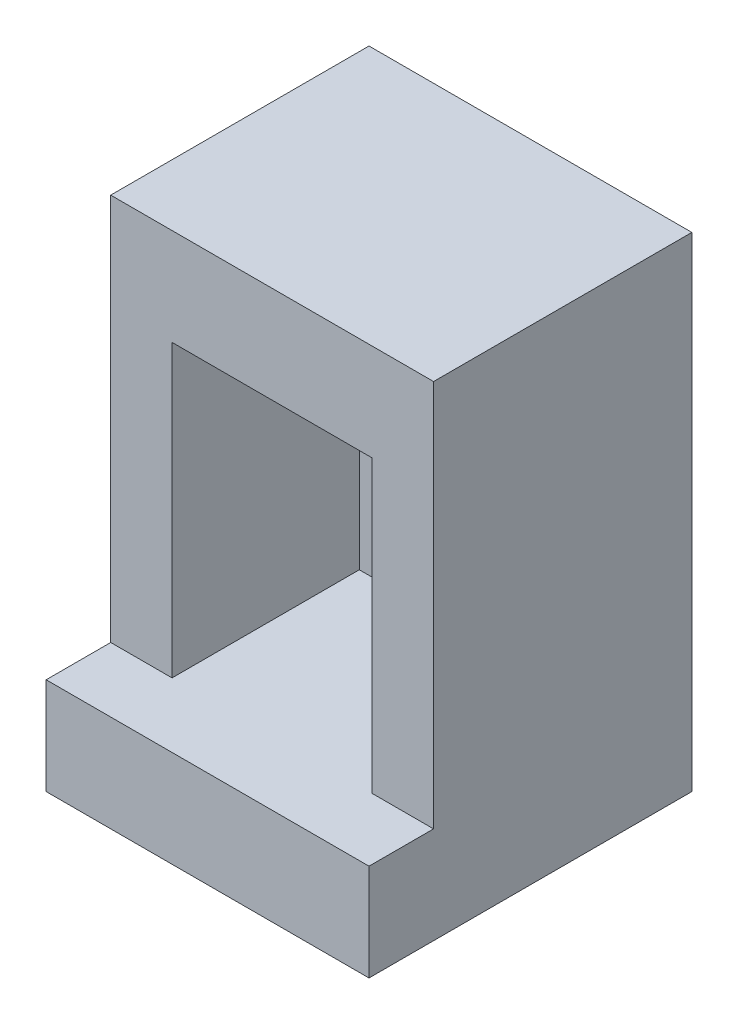
SolidWorks part; units mm, degrees
ref_plane "Front Plane" through (0, 0, 0) normal (0, 0, 1) x (1, 0, 0)
ref_plane "Top Plane" through (0, 0, 0) normal (0, 1, 0) x (1, 0, 0)
ref_plane "Right Plane" through (0, 0, 0) normal (1, 0, 0) x (0, 0, -1)
sketch "Sketch1" plane through (0, 0, 0) normal (0, 1, 0) x (1, 0, 0)
  line L1 (0, 0) -> (10, 0)
  line L2 (0, 0) -> (0, 10)
  line L3 (0, 10) -> (10, 10)
  line L4 (10, 0) -> (10, 10)
  dimension "D1" = 10
  dimension "D2" = 10
extrude "Boss-Extrude1" add sketch "Sketch1" along normal blind 3
sketch "Sketch2" plane through (0, 3, 0) normal (0, 1, 0) x (1, 0, 0)
  line L0 (10, 0) -> (10, 10) construction
  line L1 (0, 10) -> (10, 10)
  line L2 (0, 10) -> (0, 2)
  line L3 (0, 2) -> (10, 2)
  line L4 (10, 10) -> (10, 2)
  dimension "D1" = 8
extrude "Boss-Extrude2" add sketch "Sketch2" along normal blind 12
sketch "Sketch3" plane through (0, 0, -2) normal (0, 0, 1) x (1, 0, 0)
  line L0 (0, 15) -> (0, 3) construction
  line L1 (1.9, 12) -> (8.1, 12)
  line L2 (1.9, 12) -> (1.9, 3)
  line L3 (1.9, 3) -> (8.1, 3)
  line L4 (8.1, 12) -> (8.1, 3)
  line L5 (0, 3) -> (10, 3) construction
  dimension "D1" = 6.2
  dimension "D2" = 1.9
  dimension "D3" = 9
  dimension "D4" = 0
extrude "Cut-Extrude1" cut sketch "Sketch3" against normal blind 5.8
sketch "Sketch4" plane through (0, 0, -7.8) normal (0, 0, 1) x (1, 0, 0)
  line L0 (8.1, 12) -> (1.9, 12) construction
  line L1 (1.9, 12) -> (1.9, 3) construction
  circle A0 centre (5, 9.3) radius 0.75
  dimension "D1" = 1.5
  dimension "D2" = 2.7
  dimension "D3" = 3.1
extrude "Cut-Extrude2" cut sketch "Sketch4" against normal through all
